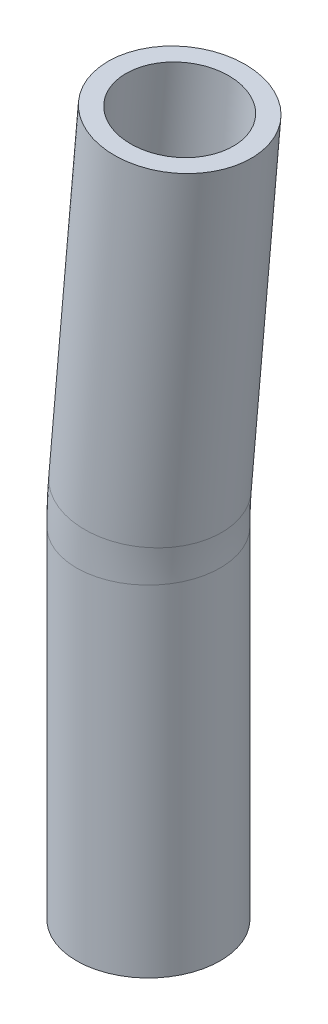
SolidWorks part; units mm, degrees
ref_plane "Front Plane" through (0, 0, 0) normal (0, 0, 1) x (1, 0, 0)
ref_plane "Top Plane" through (0, 0, 0) normal (0, 1, 0) x (1, 0, 0)
ref_plane "Right Plane" through (0, 0, 0) normal (1, 0, 0) x (0, 0, -1)
sketch "Sketch1" plane through (0, 0, 0) normal (0, 0, 1) x (1, 0, 0)
  line L0 (0, 0) -> (0, 18.9521)
  line L1 (0.0913, 21.0439) -> (1.7431, 39.9239)
  arc A0 (0, 18.9521) -> (0.0913, 21.0439) centre (24, 18.9521) cw
  point P6 (0, 20)
  dimension "D3" = 24
  dimension "D1" = 20
  dimension "D2" = 20
  dimension "D4" = 175
sketch "Sketch2" plane through (0, 0, 0) normal (0, 1, 0) x (1, 0, 0)
  circle A0 centre (0, 0) radius 4
  circle A1 centre (0, 0) radius 3
  dimension "D1" = 6
  dimension "D2" = 8
sweep "Sweep1" add profiles "Sketch2" path "Sketch1"
